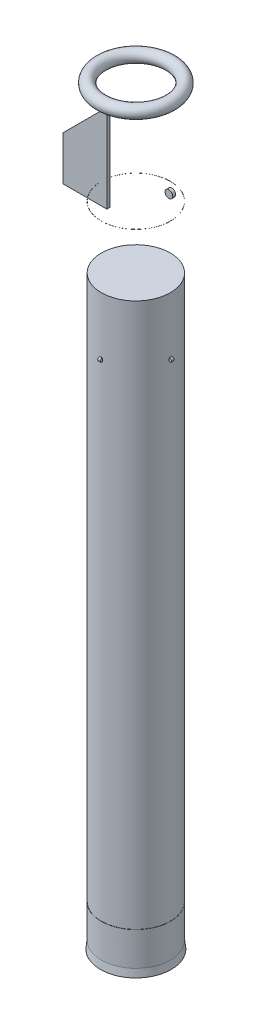
SolidWorks part; units mm, degrees
ref_plane "Front Plane" through (0, 0, 0) normal (0, 0, 1) x (1, 0, 0)
ref_plane "Top Plane" through (0, 0, 0) normal (0, 1, 0) x (1, 0, 0)
ref_plane "Right Plane" through (0, 0, 0) normal (1, 0, 0) x (0, 0, -1)
sketch "Sketch1" plane through (0, 0, 0) normal (0, 0, 1) x (1, 0, 0)
  line L0 (0, 0) -> (0, 150000) construction
  line L1 (0, 76500) -> (4500, 76500)
  line L2 (4500, 76500) -> (4500, 1000)
  line L3 (4500, 1000) -> (4620, 0)
  line L4 (4620, 0) -> (4300, 0)
  line L5 (4300, 0) -> (4300, 1500)
  line L6 (4300, 1500) -> (4300, 73000)
  line L7 (4300, 73000) -> (0, 75000)
  line L8 (0, 75000) -> (0, 76500)
revolve "Revolve1" add sketch "Sketch1" angle 360 about L0
sketch "Sketch2" plane through (0, 0, 0) normal (0, 0, 1) x (1, 0, 0)
  line L0 (0, 0) -> (0, 150000) construction
  line L1 (0, 80000) -> (4500, 80000)
  line L2 (4500, 80000) -> (4500, 76500)
  line L3 (4500, 76500) -> (-4500, 76500) construction
  line L4 (4500, 76500) -> (4320, 76500)
  line L5 (4320, 76500) -> (4500, 80000)
  line L6 (4500, 80000) -> (0, 80000)
sketch "Sketch3" plane through (0, 0, 0) normal (0, 0, 1) x (1, 0, 0)
  line L0 (0, 0) -> (0, 150000) construction
  line L1 (0, 80000) -> (4500, 80000)
  line L2 (4500, 80000) -> (4500, 116000)
  line L3 (4500, 116000) -> (4500, 81500)
  line L4 (4500, 81500) -> (0, 80000)
sketch "Sketch4" plane through (0, 0, 0) normal (0, 0, 1) x (1, 0, 0)
  line L0 (0, 0) -> (0, 4000) construction
  line L1 (0, 0) -> (0, 150000) construction
  line L2 (0, 4000) -> (0, 0)
  line L3 (0, 0) -> (580, -450)
  line L4 (580, -450) -> (580, 2700)
  line L5 (580, 2700) -> (0, 3000)
  line L6 (580, 2700) -> (1439.0909, 0)
  line L7 (-4620, 0) -> (4620, 0) construction
  line L8 (1439.0909, 0) -> (2350, -450)
  line L9 (2350, -450) -> (580, 2700)
  line L10 (580, 2700) -> (1600, 2600)
  line L11 (2350, 2600) -> (4300, 0)
  line L12 (4300, 0) -> (4150, -450)
  line L13 (4150, -450) -> (2350, 2600)
  line L14 (2350, 2600) -> (3250, 2400)
sketch "Sketch5" plane through (0, 0, 0) normal (0, 0, 1) x (1, 0, 0)
  line L0 (0, 78000) -> (0, 84000) construction
  line L1 (0, 0) -> (0, 150000) construction
  line L2 (0, 84000) -> (0, 80000)
  line L3 (0, 80000) -> (620, 79500)
  line L4 (620, 79500) -> (620, 82700)
  line L5 (620, 82700) -> (0, 83000)
  line L6 (620, 82700) -> (3850, 79500)
  line L7 (3850, 79500) -> (3750, 78800)
  line L8 (3750, 78800) -> (620, 82700)
  line L9 (620, 82700) -> (1450, 83200)
sketch "Sketch6" plane through (0, 0, 0) normal (0, 0, 1) x (1, 0, 0)
  circle A0 centre (4600, 69000) radius 220
extrude "Boss-Extrude1" add sketch "Sketch6" along normal mid plane 320
sketch "Sketch7" plane through (0, 0, 0) normal (0, 0, 1) x (1, 0, 0)
  line L0 (4800, 70600) -> (5250, 70600)
  line L1 (5250, 70600) -> (5250, 71050)
  line L2 (5250, 71050) -> (4800, 71050)
  line L3 (4800, 71050) -> (4800, 70600)
  line L4 (4800, 71050) -> (5250, 71050)
  line L5 (5250, 71050) -> (5250, 71700)
  line L6 (5250, 71700) -> (4800, 71700)
  line L7 (4800, 71700) -> (4800, 71050)
  line L8 (4800, 71700) -> (5250, 71700)
  line L9 (5250, 71700) -> (5250, 72350)
  line L10 (5250, 72350) -> (4800, 72350)
  line L11 (4800, 72350) -> (4800, 71700)
  line L12 (4800, 72350) -> (5250, 72350)
  line L13 (5250, 72350) -> (5250, 73000)
  line L14 (5250, 73000) -> (4800, 73000)
  line L15 (4800, 73000) -> (4800, 72350)
  line L16 (5250, 70600) -> (5900, 70600)
  line L17 (5900, 70600) -> (5900, 71050)
  line L18 (5900, 71050) -> (5250, 71050)
  line L19 (5250, 71050) -> (5250, 70600)
  line L20 (5250, 71050) -> (5900, 71050)
  line L21 (5900, 71050) -> (5250, 71700)
  line L22 (5250, 71700) -> (5450, 71700)
  line L23 (5450, 71700) -> (5250, 71050)
  line L24 (5450, 71700) -> (5900, 71900)
  line L25 (5900, 71900) -> (5900, 72350)
  line L26 (5900, 72350) -> (5250, 72350)
  line L27 (5250, 72350) -> (5450, 71700)
  line L28 (5250, 72350) -> (5900, 72350)
  line L29 (5900, 72350) -> (5250, 73000)
  line L30 (5250, 73000) -> (5450, 73000)
  line L31 (5450, 73000) -> (5250, 72350)
  line L32 (5900, 70600) -> (6550, 70600)
  line L33 (6550, 70600) -> (6550, 71050)
  line L34 (6550, 71050) -> (5900, 71050)
  line L35 (5900, 71050) -> (5900, 70600)
  line L36 (5900, 71050) -> (6550, 71050)
  line L37 (6550, 71050) -> (6550, 71700)
  line L38 (6550, 71700) -> (5900, 71900)
  line L39 (5900, 71900) -> (5900, 71050)
  line L40 (5900, 71900) -> (6550, 71700)
  line L41 (6550, 71700) -> (5900, 72350)
  line L42 (5900, 72350) -> (6100, 72350)
  line L43 (6100, 72350) -> (5900, 71900)
  line L44 (6100, 72350) -> (6550, 72550)
  line L45 (6550, 72550) -> (6550, 73000)
  line L46 (6550, 73000) -> (6100, 73000)
  line L47 (6100, 73000) -> (6100, 72350)
  line L48 (6550, 70600) -> (7200, 70600)
  line L49 (7200, 70600) -> (7200, 71050)
  line L50 (7200, 71050) -> (6550, 71050)
  line L51 (6550, 71050) -> (6550, 70600)
  line L52 (6550, 71050) -> (7200, 71050)
  line L53 (7200, 71050) -> (6550, 71700)
  line L54 (6550, 71700) -> (6750, 71700)
  line L55 (6750, 71700) -> (6550, 71050)
  line L56 (6750, 71700) -> (7200, 71900)
  line L57 (7200, 71900) -> (7200, 72350)
  line L58 (7200, 72350) -> (6550, 72550)
  line L59 (6550, 72550) -> (6750, 71700)
  line L60 (6550, 72550) -> (7200, 72350)
  line L61 (7200, 72350) -> (6550, 73000)
  line L62 (6550, 73000) -> (6750, 73000)
  line L63 (6750, 73000) -> (6550, 72550)
pattern_circular "CirPattern1" count 4 over 360 about axis through (0, 0, 0) along (0, 1, 0) of "Boss-Extrude1"
sketch "Sketch8" plane through (0, 0, 0) normal (0, 0, 1) x (1, 0, 0)
  line L0 (4500, 80000) -> (4500, 116000) construction
  line L1 (-3600, 93500) -> (-9350, 87750)
  line L2 (-9350, 87750) -> (-9350, 82000)
  line L3 (-9350, 82000) -> (-3600, 82000)
  line L4 (-3600, 82000) -> (-3600, 93500)
  circle A0 centre (4500, 87750) radius 500
extrude "Boss-Extrude2" add sketch "Sketch8" along normal mid plane 380
sketch "Sketch9" plane through (0, 0, 0) normal (0, 0, 1) x (1, 0, 0)
  line L0 (0, 142000) -> (5350, 136650)
  line L1 (0, 0) -> (0, 150000) construction
  line L2 (5350, 136650) -> (5350, 133500)
  line L3 (5350, 133500) -> (3200, 134500)
  line L4 (3200, 134500) -> (0, 142000)
  line L5 (0, 142000) -> (-6869.4541, 139069.0329)
  line L6 (-6869.4541, 139069.0329) -> (-6869.4541, 134500)
  line L7 (-6869.4541, 134500) -> (-3200, 134500)
  line L8 (-3200, 134500) -> (0, 142000)
  circle A0 centre (-1600, 138250) radius 1797.4468
sketch "Sketch10" plane through (0, 0, 0) normal (0, 0, 1) x (1, 0, 0)
  line L0 (0, 0) -> (0, 150000) construction
  line L1 (4500, 80000) -> (4500, 116000) construction
  circle A0 centre (4506, 5400) radius 10
  circle A1 centre (4500, 84600) radius 6
  circle A2 centre (4500, 98000) radius 800
revolve "Revolve6" add sketch "Sketch10" angle 360 about L0
sketch "Sketch11" plane through (0, 0, 0) normal (0, 0, 1) x (1, 0, 0)
  line L0 (0, 0) -> (0, 150000) construction
  line L1 (0, 150000) -> (0, 147060)
  line L2 (0, 147060) -> (2540, 137060)
  line L3 (2540, 137060) -> (2540, 126060)
  line L4 (2540, 126060) -> (4500, 116000)
  line L5 (4500, 116000) -> (4500, 80000)
  line L6 (4500, 80000) -> (4500, 80500)
  line L7 (4500, 80500) -> (4500, 116000)
  line L8 (4500, 116000) -> (2540, 126060)
  line L9 (2540, 126060) -> (2540, 137060)
  line L10 (2540, 137060) -> (0, 147060)
  line L11 (0, 147060) -> (0, 150000)
  line L12 (0, 150000) -> (0, 150060)
